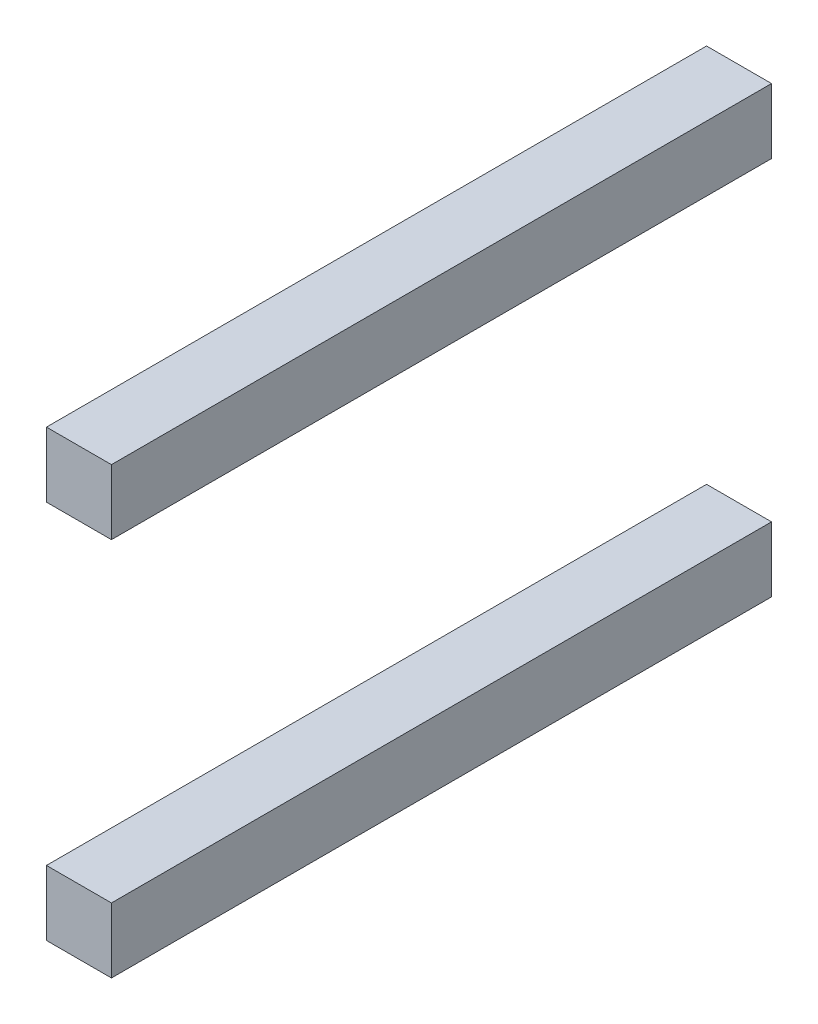
SolidWorks part; units mm, degrees
ref_plane "Front Plane" through (0, 0, 0) normal (0, 0, 1) x (1, 0, 0)
ref_plane "Top Plane" through (0, 0, 0) normal (0, 1, 0) x (1, 0, 0)
ref_plane "Right Plane" through (0, 0, 0) normal (1, 0, 0) x (0, 0, -1)
sketch "Sketch1" plane through (0, 0, 0) normal (0, 0, 1) x (1, 0, 0)
  line L0 (0, 44.45) -> (88.9, 44.45) construction
  line L1 (3.9532, 77.0255) -> (13.4782, 77.0255)
  line L2 (3.9532, 77.0255) -> (3.9532, 67.5005)
  line L3 (3.9532, 67.5005) -> (13.4782, 67.5005)
  line L4 (13.4782, 77.0255) -> (13.4782, 67.5005)
  line L5 (0, 88.9) -> (0, 0) construction
  line L6 (88.9, 9.4777) -> (88.9, 79.4223) construction
  line L7 (13.4782, 11.8745) -> (13.4782, 21.3995)
  line L8 (3.9532, 21.3995) -> (13.4782, 21.3995)
  line L9 (3.9532, 11.8745) -> (3.9532, 21.3995)
  line L10 (3.9532, 11.8745) -> (13.4782, 11.8745)
extrude "Boss-Extrude1" add sketch "Sketch1" along normal up to surface (96.7317 mm away)
